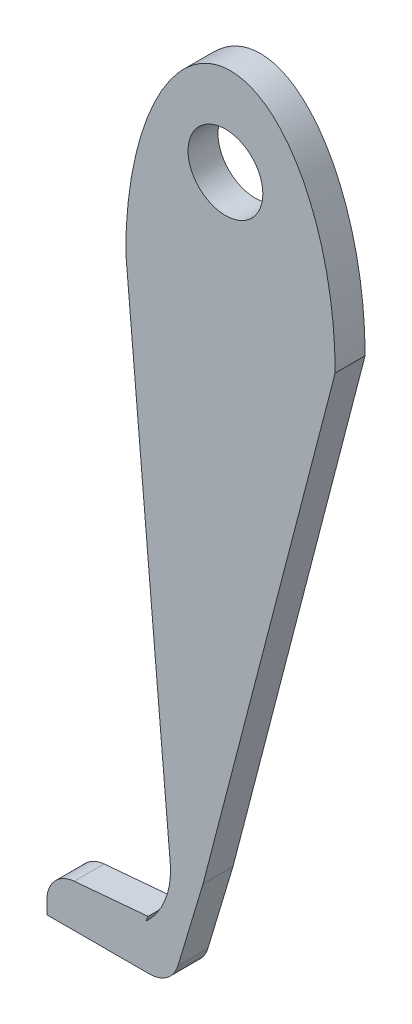
SolidWorks part; units mm, degrees
material "Pine"
ref_plane "Front Plane" through (0, 0, 0) normal (0, 0, 1) x (1, 0, 0)
ref_plane "Top Plane" through (0, 0, 0) normal (0, 1, 0) x (1, 0, 0)
ref_plane "Right Plane" through (0, 0, 0) normal (1, 0, 0) x (0, 0, -1)
sketch "Sketch1" plane through (0, 0, 0) normal (0, 0, 1) x (1, 0, 0)
  line L0 (-0.5, 0) -> (8.3365, 34)
  line L3 (-5.6635, 34) -> (-2.6803, 0)
  line L4 (-2.6803, 0) -> (-4.1719, -3.7084)
  line L5 (-4.1719, -3.7084) -> (-10.9353, -4.3018)
  line L6 (-10.9353, -4.3018) -> (-10.9353, -7)
  line L7 (-10.9353, -7) -> (-2.6063, -7)
  line L8 (-2.6063, -7) -> (-0.5, 0)
  ellipse E0 centre (1.3365, 34) end of major axis (1.3365, 48) minor radius 7 (8.3365, 34) -> (-5.6635, 34) ccw
  dimension "D1" = 34
  dimension "D2" = 14
  dimension "D3" = 14
  dimension "D4" = 34
  dimension "D5" = 7
extrude "Boss-Extrude1" add sketch "Sketch1" along normal blind 2
fillet "Fillet2" radius 2 1 edges at (-10.9353, -4.3018, 1)
fillet "Fillet3" radius 2 1 edges at (-2.6063, -7, 1)
sketch "Sketch4" plane through (0, 0, 2) normal (0, 0, 1) x (1, 0, 0)
  line L0 (-2.6803, 0) -> (-4.1719, -3.7084) construction
  line L1 (-2.6803, 0) -> (-4.3112, -4.0546)
  arc A0 (-2.6803, 0) -> (-4.3112, -4.0546) centre (-7.7792, -0.3044) cw
extrude "Cut-Extrude4" cut sketch "Sketch4" against normal blind 2
sketch "Sketch2" plane through (0, 0, 2) normal (0, 0, 1) x (1, 0, 0)
  circle A1 centre (1, 41.95) radius 2.5
  dimension "D1" = 5
extrude "Cut-Extrude5" cut sketch "Sketch2" against normal blind 2
